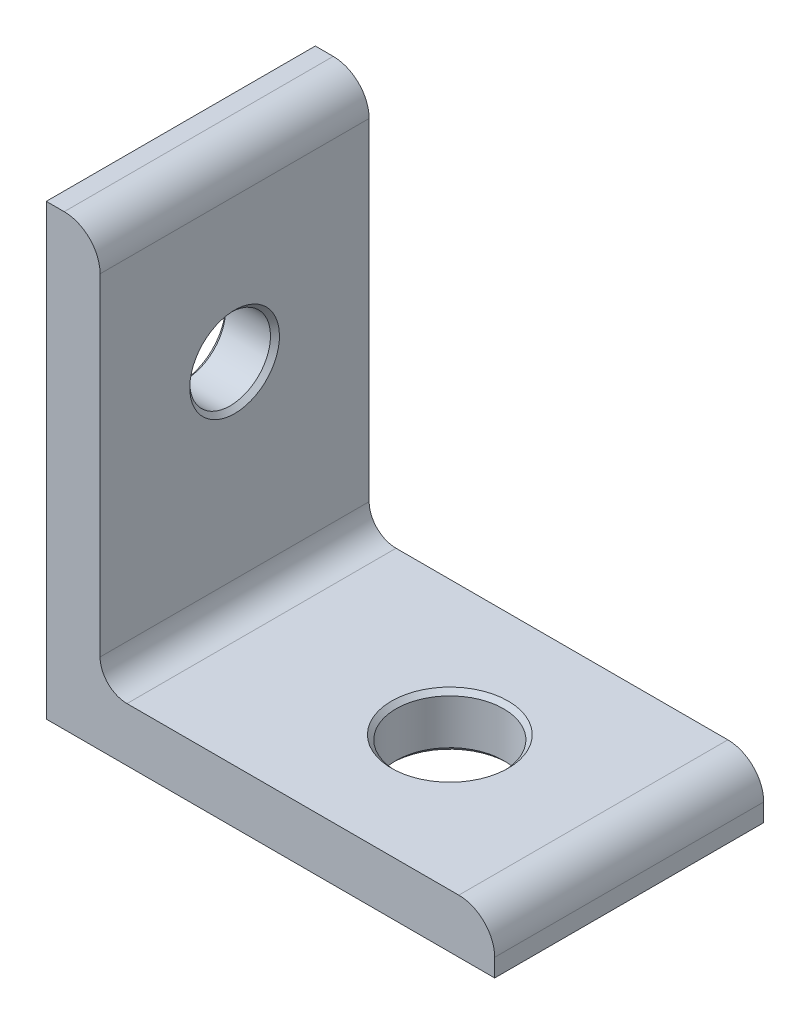
SolidWorks part; units mm, degrees
ref_plane "Front Plane" through (0, 0, 0) normal (0, 0, 1) x (1, 0, 0)
ref_plane "Top Plane" through (0, 0, 0) normal (0, 1, 0) x (1, 0, 0)
ref_plane "Right Plane" through (0, 0, 0) normal (1, 0, 0) x (0, 0, -1)
ref_plane "Plan1" through (0, 0, 20.5) normal (0, 0, 1) x (1, 0, 0)
sketch "Esquisse1" plane through (0, 0, 20.5) normal (0, 0, 1) x (1, 0, 0)
  line L0 (50, 0) -> (50, 50)
  line L1 (50, 50) -> (0, 50)
  line L2 (0, 50) -> (0, 0)
  line L3 (0, 0) -> (50, 0)
  dimension "D1" = 50
extrude "Boss.-Extru.1" add sketch "Esquisse1" against normal blind 30
sketch "Esquisse2" plane through (0, 0, -9.5) normal (0, 0, -1) x (-1, 0, 0)
  line L0 (-6, 6) -> (-6, 90)
  line L1 (-6, 90) -> (-90, 90)
  line L2 (-90, 90) -> (-90, 6)
  line L3 (-90, 6) -> (-6, 6)
extrude "Enlèv. mat.-Extru.1" cut sketch "Esquisse2" against normal through all
hole_wizard "Diamètre du perçage Ø12.0 (12)1" positions "Esquisse8" profile "Esquisse7" hole size "Ø12.0" standard "Ansi Metric" end condition through all
sketch "Esquisse8" plane through (0, 6, 0) normal (0, 1, 0) x (1, 0, 0)
  line L0 (50, -20.5) -> (50, 9.5) construction
  line L1 (50, 9.5) -> (6, 9.5) construction
  point P0 (30, -5.5)
  dimension "D1" = 20
  dimension "D2" = 15
sketch "Esquisse7" plane through (30, 6, 5.5) normal (1, 0, 0) x (0, 0, 1)
  line L0 (0, 0) -> (0, 6)
  line L1 (0, 6) -> (6, 6)
  line L2 (6, 6) -> (6, 0)
  line L5 (6, 0) -> (0, 0)
  line L11 (0, -6.35) -> (0, 107.95) construction
  dimension "Diamètre du perçage jusqu'au prochain" = 12
  dimension "Profondeur du perçage jusqu'au prochain" = 6
hole_wizard "Diamètre du perçage Ø9.0 (9)2" positions "Esquisse10" profile "Esquisse9" hole size "Ø9.0" standard "Ansi Metric" end condition through all
sketch "Esquisse10" plane through (6, 0, 0) normal (1, 0, 0) x (0, 0, -1)
  line L0 (9.5, 50) -> (-20.5, 50) construction
  line L1 (-20.5, 6) -> (-20.5, 50) construction
  point P0 (-5.5, 30)
  dimension "D1" = 20
  dimension "D2" = 15
sketch "Esquisse9" plane through (6, 30, 5.5) normal (0, 1, 0) x (0, 0, -1)
  line L0 (0, 0) -> (0, 6)
  line L1 (0, 6) -> (4.5, 6)
  line L2 (4.5, 6) -> (4.5, 0)
  line L5 (4.5, 0) -> (0, 0)
  line L11 (0, -6.35) -> (0, 107.95) construction
  dimension "Diamètre du perçage jusqu'au prochain" = 9
  dimension "Profondeur du perçage jusqu'au prochain" = 6
chamfer "Chanfrein1" distance 0.5 angle 45 4 edges at (0, 30, 1) (6, 30, 1) (30, 0, 11.5) (30, 6, 11.5)
fillet "Congé1" radius 3 1 edges at (6, 6, 5.5)
fillet "Congé2" radius 4 2 edges at (6, 50, 5.5) (50, 6, 5.5)
